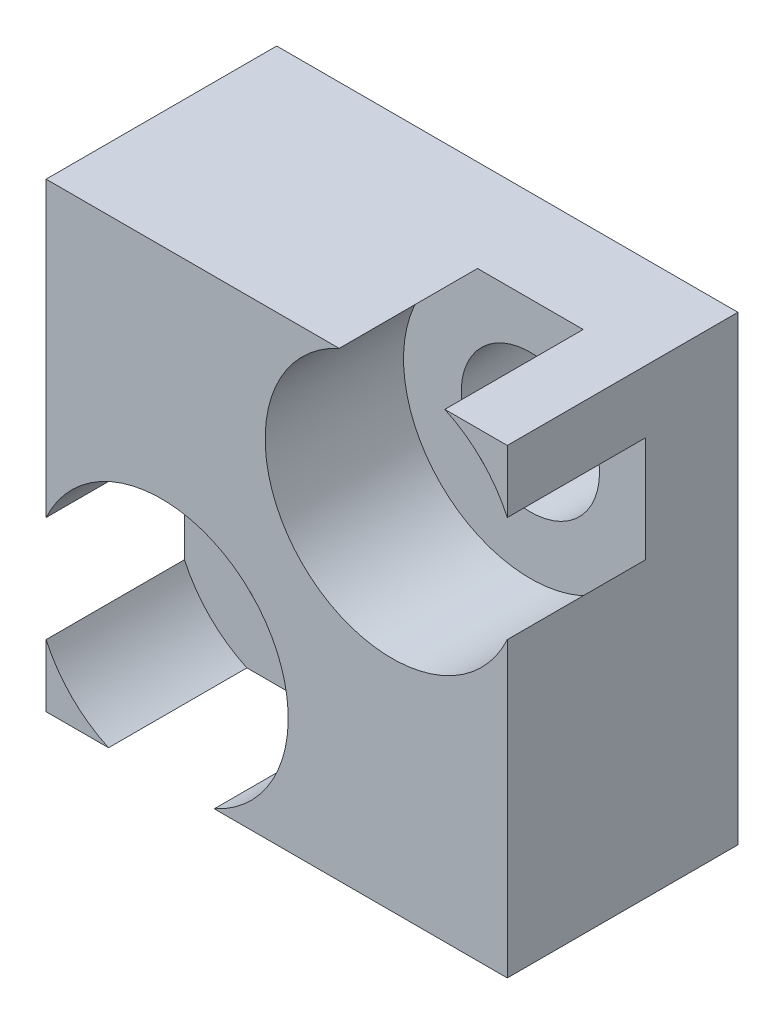
SolidWorks part; units mm, degrees
ref_plane "前视基准面" through (0, 0, 0) normal (0, 0, 1) x (1, 0, 0)
ref_plane "上视基准面" through (0, 0, 0) normal (0, 1, 0) x (1, 0, 0)
ref_plane "右视基准面" through (0, 0, 0) normal (1, 0, 0) x (0, 0, -1)
other "Configuration Table"
sketch "草图1" plane through (0, 0, 0) normal (0, 0, 1) x (1, 0, 0)
  line L1 (0, 0) -> (20, 0)
  line L2 (0, 0) -> (0, 20)
  line L3 (0, 20) -> (20, 20)
  line L4 (20, 0) -> (20, 20)
extrude "BaseBox" add sketch "草图1" along normal blind 10
sketch "草图2" plane through (0, 0, 10) normal (0, 0, 1) x (1, 0, 0)
  point P0 (5, 5)
  point P1 (15, 15)
hole_wizard "Hole_TwoPoint_sketch_points_ext" positions "3D草图1" profile "草图3" counterbore size "M6" standard "ISO" end condition through all
sketch3d "3D草图1"
  point P0 (15, 15, 10)
  point P2 (5, 5, 10)
sketch "草图3" plane through (15, 15, 10) normal (1, 0, 0) x (0, -1, 0)
  line L0 (0, 0) -> (0, 10)
  line L1 (0, 10) -> (3, 10)
  line L3 (3, 10) -> (3, 6)
  line L4 (3, 6) -> (5.5, 6)
  line L5 (5.5, 6) -> (5.5, 0)
  line L7 (5.5, 0) -> (0, 0)
  line L11 (0, -6.35) -> (0, 107.95) construction
  dimension "通孔孔直径" = 6
  dimension "通孔孔深度" = 10
  dimension "柱形沉头孔直径" = 11
  dimension "柱形沉头孔深度" = 6
